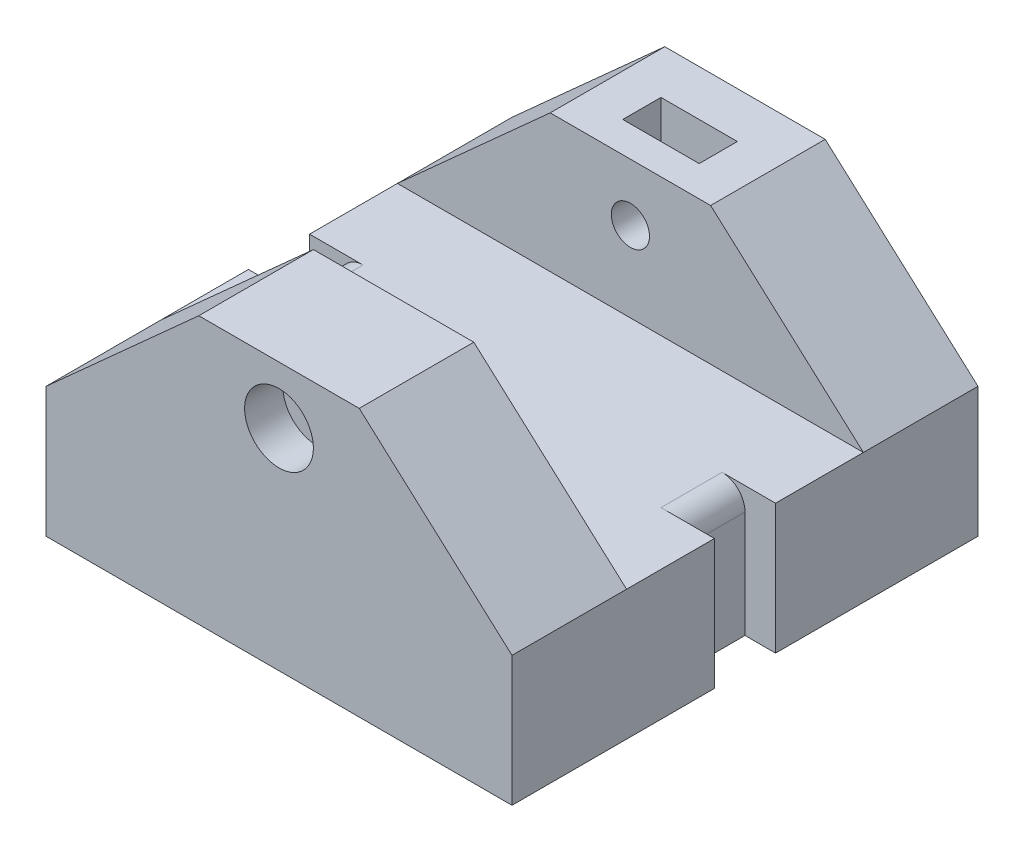
SolidWorks part; units mm, degrees
ref_plane "Ön Düzlem" through (0, 0, 0) normal (0, 0, 1) x (1, 0, 0)
ref_plane "Üst Düzlem" through (0, 0, 0) normal (0, 1, 0) x (1, 0, 0)
ref_plane "Sağ Düzlem" through (0, 0, 0) normal (1, 0, 0) x (0, 0, -1)
sketch "Sketch1" plane through (0, 0, 0) normal (0, 1, 0) x (1, 0, 0)
  line L1 (-41, 20.5) -> (0, 20.5)
  line L2 (-41, 20.5) -> (-41, -20.5)
  line L3 (-41, -20.5) -> (0, -20.5)
  line L4 (0, 20.5) -> (0, -20.5)
  line L5 (-51, 30.5) -> (10, 30.5)
  line L6 (-51, 30.5) -> (-51, -30.5)
  line L7 (-51, -30.5) -> (10, -30.5)
  line L8 (10, 30.5) -> (10, -30.5)
  point P4 (0, 0)
  dimension "D1" = 41
  dimension "D2" = 61
  dimension "D3" = 10
  dimension "D4" = 10
extrude "Boss-Extrude1" add sketch "Sketch1" along normal blind 15
sketch "Sketch2" plane through (0, 15, 0) normal (0, 1, 0) x (1, 0, 0)
  line L1 (-51, 30.5) -> (10, 30.5)
  line L2 (-51, 30.5) -> (-51, -30.5)
  line L3 (-51, -30.5) -> (10, -30.5)
  line L4 (10, 30.5) -> (10, -30.5)
extrude "Boss-Extrude2" add sketch "Sketch2" along normal blind 20
sketch "Sketch3" plane through (0, 0, 30.5) normal (0, 0, 1) x (1, 0, 0)
  line L1 (-51, 35) -> (-51, 0) construction
  line L2 (10, 35) -> (10, 0) construction
  line L4 (-51, 17) -> (-31, 35)
  line L5 (-51, 35) -> (10, 35) construction
  line L6 (-31, 35) -> (-51, 35)
  line L7 (-51, 35) -> (-51, 17)
  line L8 (-10, 35) -> (10, 17)
  line L9 (10, 17) -> (10, 35)
  line L10 (10, 35) -> (-10, 35)
  circle A0 centre (-20.5, 27.5) radius 2.5
  dimension "D2" = 5
  dimension "D1" = 17
  dimension "D3" = 10.5
  dimension "D4" = 20
  dimension "D5" = 7.5
  dimension "20" = 20
  dimension "D6" = 10.5
  dimension "D7" = 17
extrude "Cut-Extrude1" cut sketch "Sketch3" against normal blind 90
sketch "Sketch5" plane through (10, 0, 0) normal (1, 0, 0) x (0, 0, -1)
  line L2 (30.5, 35) -> (-30.5, 35) construction
  line L3 (-15.5, 35) -> (15.5, 35)
  line L4 (-15.5, 35) -> (-15.5, 17)
  line L5 (-15.5, 17) -> (15.5, 17)
  line L6 (15.5, 35) -> (15.5, 17)
  line L7 (30.5, 17) -> (-30.5, 17) construction
  line L8 (-30.5, 35) -> (-30.5, 17) construction
  line L9 (30.5, 35) -> (30.5, 17) construction
  dimension "D1" = 15
  dimension "D2" = 15
extrude "Cut-Extrude2" cut sketch "Sketch5" against normal blind 90
sketch "Sketch6" plane through (0, 17, 0) normal (0, 1, 0) x (1, 0, 0)
  line L0 (-51, 4) -> (-47, 4)
  line L1 (6, 4) -> (10, 4)
  line L2 (6, 4) -> (6, -4)
  line L3 (6, -4) -> (10, -4)
  line L4 (10, 4) -> (10, -4)
  line L5 (-51, 4) -> (-51, -4)
  line L6 (-51, -4) -> (-47, -4)
  line L7 (-47, 4) -> (-47, -4)
  line L8 (10, -15.5) -> (10, 15.5) construction
  line L10 (-51, 15.5) -> (-51, -15.5) construction
  point P10 (10, 0)
  point P11 (10, 0)
  point P14 (-51, 0)
  point P15 (-51, 0)
  dimension "D1" = 8
  dimension "D2" = 4
  dimension "D3" = 4
  dimension "D4" = 8
extrude "Cut-Extrude3" cut sketch "Sketch6" against normal blind 90
sketch "Sketch7" plane through (0, 0, 30.5) normal (0, 0, 1) x (1, 0, 0)
  circle A0 centre (-20.5, 27.5) radius 4.5
  dimension "D1" = 9
extrude "Cut-Extrude4" cut sketch "Sketch7" against normal blind 5
sketch "Sketch8" plane through (0, 35, 0) normal (0, 1, 0) x (1, 0, 0)
  line L0 (-31, 15.5) -> (-10, 15.5) construction
  line L1 (-25.5, 24.5) -> (-15.5, 24.5)
  line L2 (-25.5, 24.5) -> (-25.5, 19.5)
  line L3 (-25.5, 19.5) -> (-15.5, 19.5)
  line L4 (-15.5, 24.5) -> (-15.5, 19.5)
  line L5 (-10, 30.5) -> (-31, 30.5) construction
  point P8 (-20.5, 30.5)
  point P9 (-20.5, 24.5)
  dimension "D1" = 5
  dimension "D2" = 10
  dimension "D3" = 4
extrude "Cut-Extrude5" cut sketch "Sketch8" against normal blind 13
fillet "Fillet1" radius 3 2 edges at (6, 17, 0) (-47, 17, 0)
